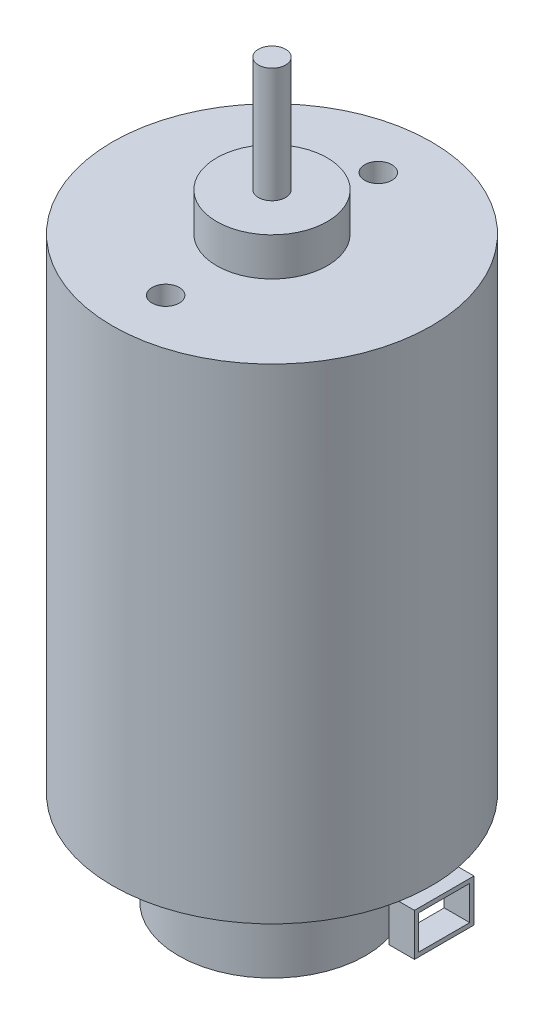
SolidWorks part; units mm, degrees
ref_plane "前视基准面" through (0, 0, 0) normal (0, 0, 1) x (1, 0, 0)
ref_plane "上视基准面" through (0, 0, 0) normal (0, 1, 0) x (1, 0, 0)
ref_plane "右视基准面" through (0, 0, 0) normal (1, 0, 0) x (0, 0, -1)
sketch "草图1" plane through (0, 0, 0) normal (0, 1, 0) x (1, 0, 0)
  circle A0 centre (0, 0) radius 18.75
extrude "凸台-拉伸1" add sketch "草图1" along normal blind 57
sketch "草图2" plane through (0, 0, 0) normal (0, -1, 0) x (1, 0, 0)
  circle A0 centre (0, 0) radius 11
extrude "凸台-拉伸2" add sketch "草图2" along normal blind 11
sketch "草图3" plane through (0, 0, 0) normal (0, -1, 0) x (1, 0, 0)
  line L1 (17.25, -3.5) -> (20.25, -3.5)
  line L2 (17.25, -3.5) -> (17.25, 3.5)
  line L3 (17.25, 3.5) -> (20.25, 3.5)
  line L4 (20.25, -3.5) -> (20.25, 3.5)
  line L5 (17.25, -3.5) -> (20.25, 3.5) construction
  line L6 (17.25, 3.5) -> (20.25, -3.5) construction
  circle A0 centre (0, 0) radius 18.75 construction
  point P0 (18.75, 0)
extrude "凸台-拉伸3" add sketch "草图3" along normal blind 5
sketch "草图4" plane through (20.25, 0, 0) normal (1, 0, 0) x (0, 0, -1)
  line L1 (3, -4.5) -> (-3, -4.5)
  line L2 (3, -4.5) -> (3, -0.5)
  line L3 (3, -0.5) -> (-3, -0.5)
  line L4 (-3, -4.5) -> (-3, -0.5)
  line L5 (3, -4.5) -> (-3, -0.5) construction
  line L6 (3, -0.5) -> (-3, -4.5) construction
  point P0 (0, -2.5)
extrude "切除-拉伸1" cut sketch "草图4" against normal blind 3
sketch "草图5" plane through (0, 57, 0) normal (0, 1, 0) x (1, 0, 0)
  circle A0 centre (0, 0) radius 6.5
extrude "凸台-拉伸4" add sketch "草图5" along normal blind 4.5
sketch "草图6" plane through (0, 57, 0) normal (0, 1, 0) x (1, 0, 0)
  circle A0 centre (0, -12.5) radius 1.6
  circle A1 centre (0, 12.5) radius 1.6
extrude "切除-拉伸2" cut sketch "草图6" against normal blind 4
sketch "草图7" plane through (0, 61.5, 0) normal (0, 1, 0) x (1, 0, 0)
  circle A0 centre (0, 0) radius 1.6
extrude "凸台-拉伸5" add sketch "草图7" along normal blind 13.5
